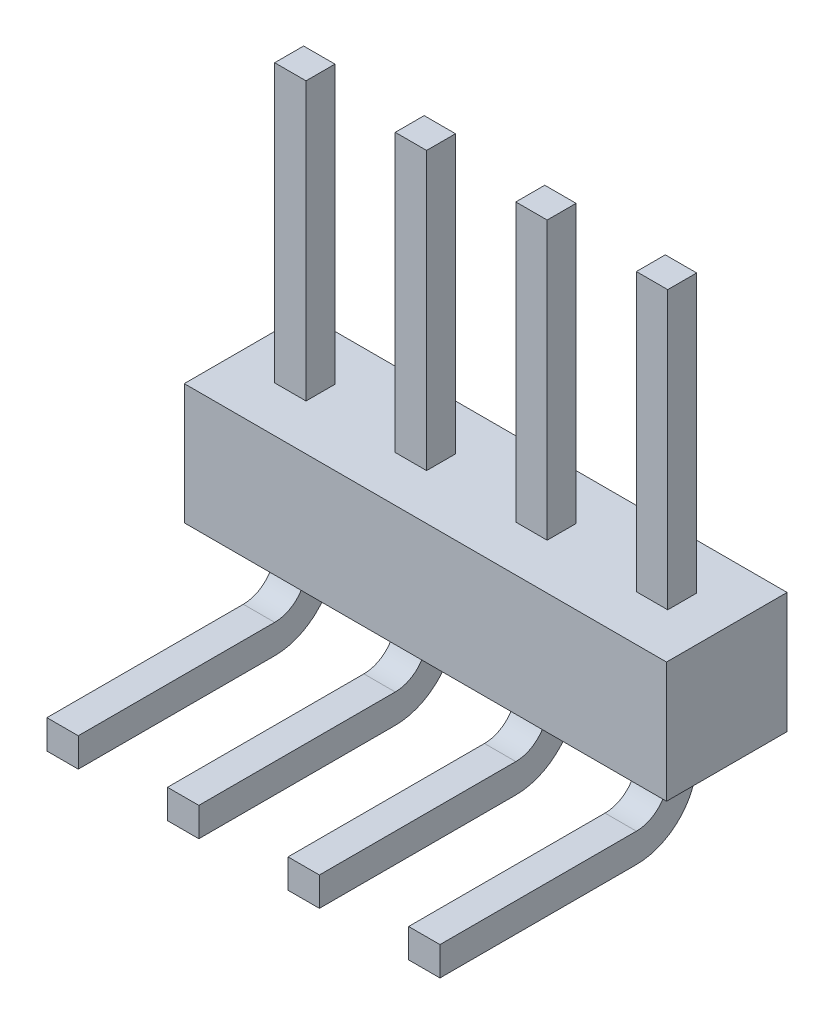
SolidWorks part; units mm, degrees
material "Nylon 6/10"
ref_plane "Front Plane" through (0, 0, 0) normal (0, 0, 1) x (1, 0, 0)
ref_plane "Top Plane" through (0, 0, 0) normal (0, 1, 0) x (1, 0, 0)
ref_plane "Right Plane" through (0, 0, 0) normal (1, 0, 0) x (0, 0, -1)
sketch "Sketch2" plane through (0, 0, 0) normal (1, 0, 0) x (0, 0, -1)
  line L1 (-1.27, -1.27) -> (1.27, -1.27)
  line L2 (-1.27, -1.27) -> (-1.27, 1.27)
  line L3 (-1.27, 1.27) -> (1.27, 1.27)
  line L4 (1.27, -1.27) -> (1.27, 1.27)
  line L5 (-1.27, -1.27) -> (1.27, 1.27) construction
  line L6 (-1.27, 1.27) -> (1.27, -1.27) construction
  point P0 (0, 0)
  dimension "D1" = 2.54
extrude "Boss-Extrude1" add sketch "Sketch2" along normal mid plane 10.16
ref_plane "Plane1" through (3.81, 0, 0) normal (1, 0, 0) x (0, 0, -1)
sketch "Sketch3" plane through (3.81, 0, 0) normal (1, 0, 0) x (0, 0, -1)
  line L0 (-0.3048, 7.112) -> (-0.3048, -1.778)
  line L1 (-0.9652, -2.4384) -> (-5.1032, -2.4384)
  line L2 (-5.1032, -2.4384) -> (-5.1032, -3.048)
  line L3 (-5.1032, -3.048) -> (-0.9652, -3.048)
  line L4 (0.3048, -1.778) -> (0.3048, 7.112)
  line L5 (0.3048, 7.112) -> (-0.3048, 7.112)
  line L6 (1.27, 1.27) -> (-1.27, 1.27) construction
  arc A0 (-0.9652, -3.048) -> (0.3048, -1.778) centre (-0.9652, -1.778) ccw
  arc A1 (-0.9652, -2.4384) -> (-0.3048, -1.778) centre (-0.9652, -1.778) ccw
  point P12 (0, 7.112)
  dimension "D1" = 1.27
  dimension "D2" = 10.16
  dimension "D3" = 5.842
  dimension "D4" = 0.6096
extrude "Boss-Extrude2" add sketch "Sketch3" along normal mid plane 0.6604 contours L4 L5 L0 A1 L1 L2 L3 A0
pattern_linear "LPattern1" count 4 spacing 2.54 along (-1, 0, 0) of "Boss-Extrude2"
